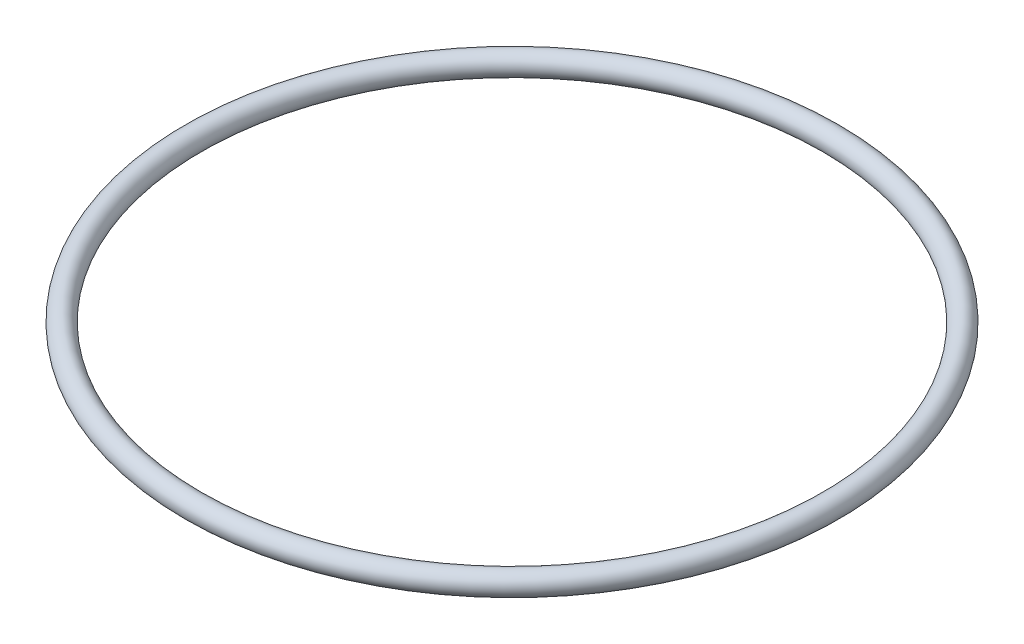
SolidWorks part; units mm, degrees
material "NBR"
ref_plane "Ön Düzlem" through (0, 0, 0) normal (0, 0, 1) x (1, 0, 0)
ref_plane "Üst Düzlem" through (0, 0, 0) normal (0, 1, 0) x (1, 0, 0)
ref_plane "Sağ Düzlem" through (0, 0, 0) normal (1, 0, 0) x (0, 0, -1)
sketch "Çizim1" plane through (0, 0, 0) normal (0, 0, 1) x (1, 0, 0)
  line L0 (-49.01, 0) -> (49.01, 0)
  line L1 (0, 0) -> (0, 15.3913)
  circle A1 centre (-50.775, 0) radius 1.765
  point P3 (0, 0)
  dimension "D2" = 3.53
  dimension "D1" = 98.02
revolve "Döndür1" add sketch "Çizim1" angle 360 about L1
sketch "Çizim2" plane through (0, 0, 0) normal (0, 1, 0) x (1, 0, 0)
  circle A0 centre (0, 0) radius 85.385
